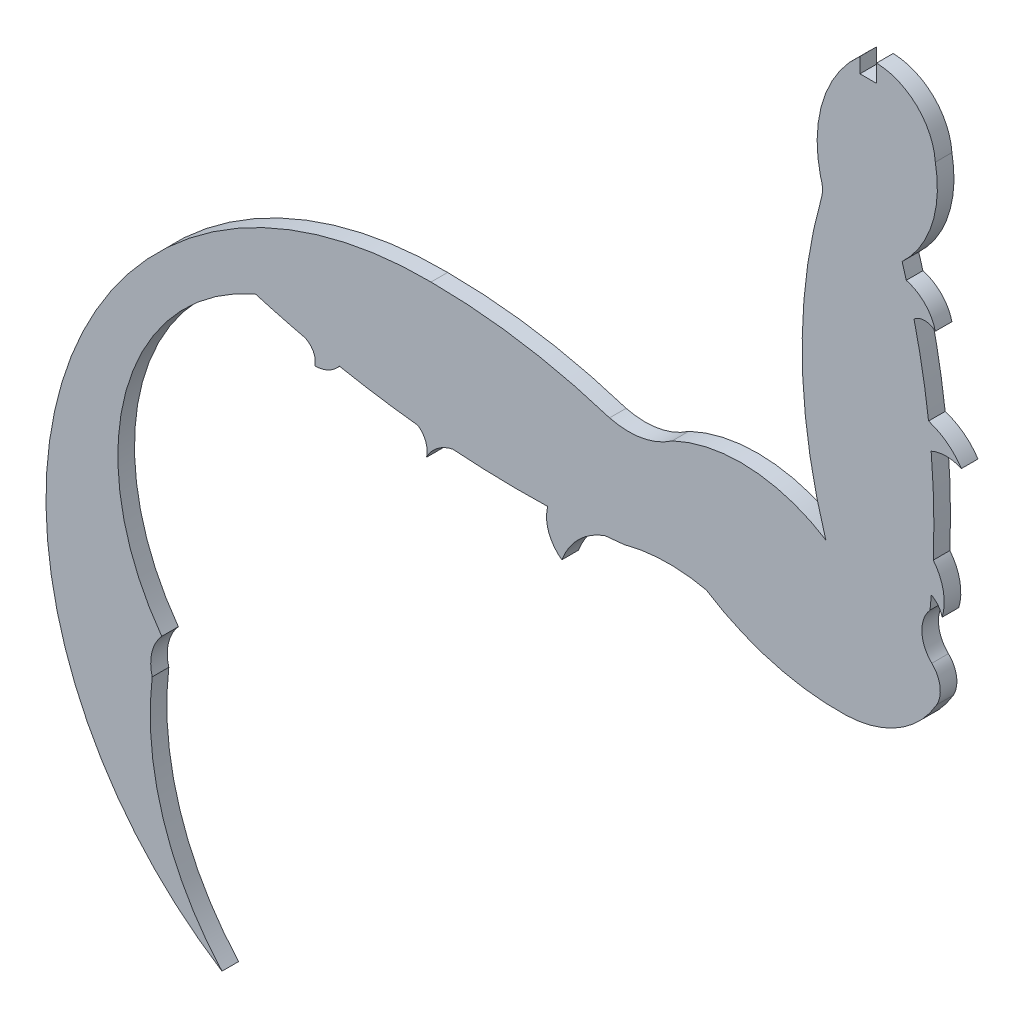
SolidWorks part; units mm, degrees
ref_plane "Front Plane" through (0, 0, 0) normal (0, 0, 1) x (1, 0, 0)
ref_plane "Top Plane" through (0, 0, 0) normal (0, 1, 0) x (1, 0, 0)
ref_plane "Right Plane" through (0, 0, 0) normal (1, 0, 0) x (0, 0, -1)
sketch "Sketch1" plane through (0, 0, 0) normal (0, 0, 1) x (1, 0, 0)
  line L3 (-1.524, 93.9963) -> (0, 93.9963)
  line L4 (0, 93.9963) -> (0, 95.6149)
  line L5 (-1.524, 93.9963) -> (-1.524, 95.3808)
  arc A0 (-1.524, 95.3808) -> (-5.1352, 83.9984) centre (6.107, 86.6957) ccw
  arc A1 (2.7276, 79.7096) -> (5.3943, 76.9897) centre (1.7545, 76.0884) cw
  arc A2 (-5.0554, 82.3833) -> (-4.6596, 55.3804) centre (40.5076, 69.5468) ccw
  arc A3 (-5.1352, 83.9984) -> (-5.0554, 82.3833) centre (-7.5002, 83.0721) cw
  arc A4 (0, 95.6149) -> (5.3943, 90.432) centre (-0.1739, 90.0353) cw
  arc A5 (5.3943, 90.432) -> (2.3445, 81.0105) centre (-4.6596, 88.4821) cw
  arc A6 (2.3445, 81.0105) -> (2.7276, 79.7096) centre (-61.5546, 61.4842) cw
  arc A7 (4.9034, 54.5771) -> (5.0729, 50.4429) centre (7.1548, 52.5988) ccw
  arc A8 (5.5108, 47.3503) -> (-2.8177, 42.3742) centre (-3.094, 52.2944) cw
  arc A9 (5.0729, 50.4429) -> (5.5108, 47.3503) centre (3.3084, 48.6157) cw
  arc A10 (-2.8177, 42.3742) -> (-15.6389, 45.9204) centre (-3.449, 65.042) cw
  arc A11 (-15.6389, 45.9204) -> (-23.1281, 45.7653) centre (-19.0709, 30.7507) ccw
  arc A12 (-23.1281, 45.7653) -> (-24.9174, 45.5871) centre (-32.6045, 131.8147) cw
  arc A13 (-4.6596, 55.3804) -> (-18.7504, 56.2078) centre (-12.4542, 43.035) ccw
  arc A14 (-18.7504, 56.2078) -> (-24.5068, 55.1579) centre (-22.7617, 61.8956) cw
  arc A15 (-24.5068, 55.1579) -> (-40.8905, 57.7645) centre (-40.977, 4.428) ccw
  arc A16 (-40.8905, 57.7645) -> (-60.0772, -6.6073) centre (-41.311, 22.8445) ccw
  arc A17 (-56.9935, 48.7516) -> (-65.6062, 17.2456) centre (-48.7719, 29.5739) ccw
  arc A18 (-65.6062, 17.2456) -> (-66.4844, 13.5807) centre (-62.6731, 14.605) ccw
  arc A19 (-66.4844, 13.5807) -> (-60.0772, -6.6073) centre (-41.1374, 10.5145) ccw
  arc A20 (5.3943, 76.9897) -> (3.4373, 76.9897) centre (4.4158, 75.8663) ccw
  arc A21 (4.7731, 69.5468) -> (7.7862, 67.272) centre (3.0883, 64.1824) cw
  arc A22 (7.7862, 67.272) -> (5.0102, 67.272) centre (6.3982, 64.1485) ccw
  arc A23 (5.2035, 58.7047) -> (6.0224, 54.5771) centre (1.6923, 55.8631) cw
  arc A24 (6.0224, 54.5771) -> (5.0245, 55.8631) centre (4.0308, 54.0617) ccw
  arc A25 (5.0245, 55.8631) -> (4.9034, 54.5771) centre (-61.5546, 61.4842) cw
  arc A26 (5.0102, 67.272) -> (5.2035, 58.7047) centre (-61.5546, 61.4842) cw
  arc A27 (3.4373, 76.9897) -> (4.7731, 69.5468) centre (-61.5546, 61.4842) cw
  arc A28 (-24.9174, 45.5871) -> (-28.8834, 41.6879) centre (-22.7361, 39.4019) ccw
  arc A29 (-28.8834, 41.6879) -> (-30.1791, 45.2791) centre (-26.9253, 44.4237) cw
  arc A30 (-38.9011, 45.4744) -> (-41.311, 43.6189) centre (-38.1582, 42.0168) ccw
  arc A31 (-41.311, 43.6189) -> (-42.0812, 45.7654) centre (-43.2737, 44.1261) ccw
  arc A32 (-52.4983, 47.5619) -> (-51.5601, 45.7654) centre (-53.0552, 46.1279) cw
  arc A33 (-51.5601, 45.7654) -> (-49.3042, 46.8711) centre (-51.5866, 48.6735) ccw
  arc A34 (-52.4983, 47.5619) -> (-56.9935, 48.7516) centre (-32.6045, 131.8147) cw
  arc A35 (-42.0812, 45.7654) -> (-49.3042, 46.8711) centre (-32.6045, 131.8147) cw
  arc A36 (-30.1791, 45.2791) -> (-38.9011, 45.4744) centre (-32.6045, 131.8147) cw
  dimension "D1" = 2.54
  dimension "D2" = 2.54
extrude "Boss-Extrude1" add sketch "Sketch1" along normal blind 1.524
